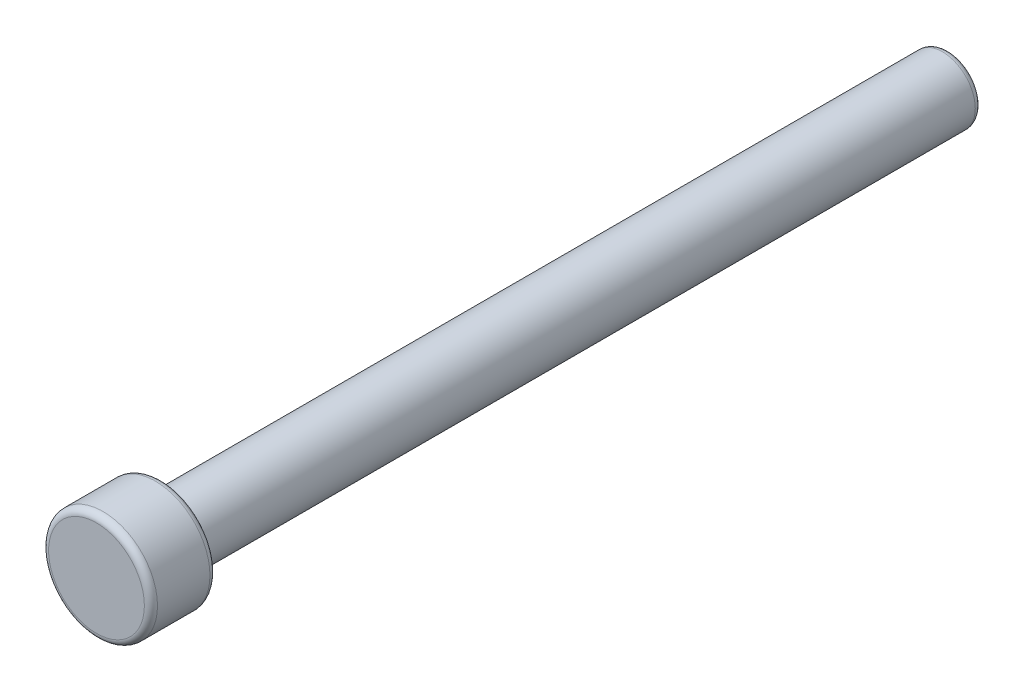
SolidWorks part; units mm, degrees
ref_plane "Front Plane" through (0, 0, 0) normal (0, 0, 1) x (1, 0, 0)
ref_plane "Top Plane" through (0, 0, 0) normal (0, 1, 0) x (1, 0, 0)
ref_plane "Right Plane" through (0, 0, 0) normal (1, 0, 0) x (0, 0, -1)
sketch "Sketch1" plane through (0, 0, 0) normal (0, 0, 1) x (1, 0, 0)
  circle A0 centre (0, 0) radius 2.5
  dimension "D1" = 5
extrude "Boss-Extrude1" add sketch "Sketch1" along normal blind 60
sketch "Sketch2" plane through (0, 0, 60) normal (0, 0, 1) x (1, 0, 0)
  circle A0 centre (0, 0) radius 4.15
  dimension "D1" = 8.3
extrude "Boss-Extrude2" add sketch "Sketch2" along normal blind 5
fillet "Fillet1" radius 0.5 4 edges at (2.5, 0, 60) (2.5, 0, 0) (4.15, 0, 65) (4.15, 0, 60)
